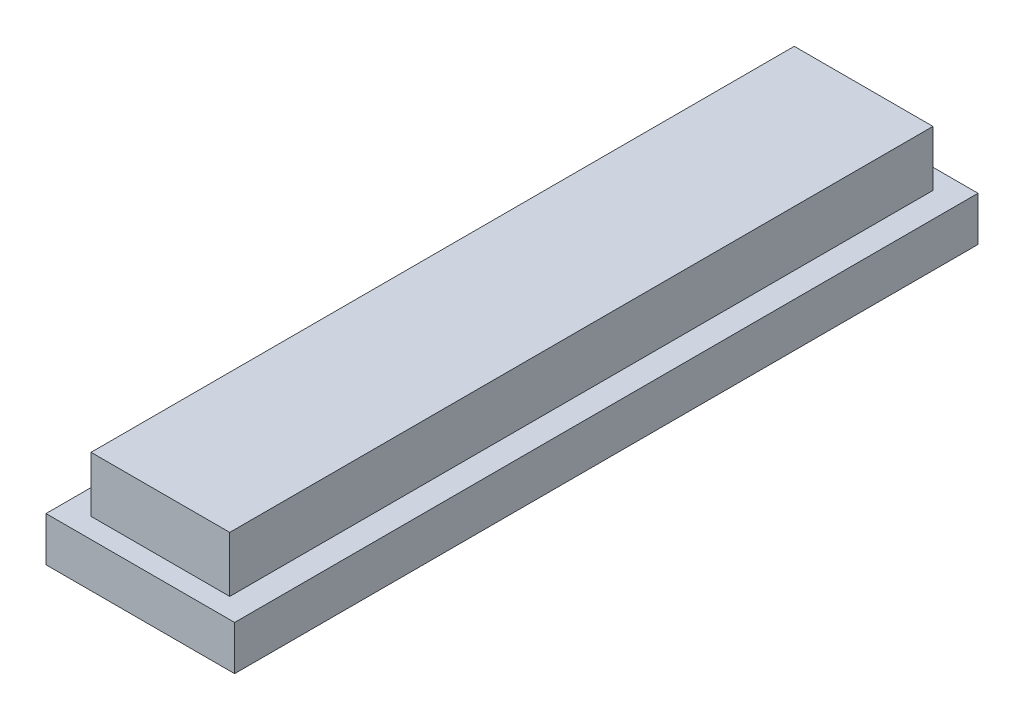
SolidWorks part; units mm, degrees
ref_plane "Front Plane" through (0, 0, 0) normal (0, 0, 1) x (1, 0, 0)
ref_plane "Top Plane" through (0, 0, 0) normal (0, 1, 0) x (1, 0, 0)
ref_plane "Right Plane" through (0, 0, 0) normal (1, 0, 0) x (0, 0, -1)
sketch "Sketch1" plane through (0, 0, 0) normal (0, 1, 0) x (1, 0, 0)
  line L1 (8.5, 33.5) -> (-8.5, 33.5)
  line L2 (8.5, 33.5) -> (8.5, -33.5)
  line L3 (8.5, -33.5) -> (-8.5, -33.5)
  line L4 (-8.5, 33.5) -> (-8.5, -33.5)
  line L5 (8.5, 33.5) -> (-8.5, -33.5) construction
  line L6 (8.5, -33.5) -> (-8.5, 33.5) construction
  point P0 (0, 0)
  dimension "D1" = 17
  dimension "D2" = 67
extrude "Boss-Extrude1" add sketch "Sketch1" along normal blind 4
sketch "Sketch2" plane through (0, 4, 0) normal (0, 1, 0) x (1, 0, 0)
  line L1 (6.25, 31.69) -> (-6.25, 31.69)
  line L2 (6.25, 31.69) -> (6.25, -31.69)
  line L3 (6.25, -31.69) -> (-6.25, -31.69)
  line L4 (-6.25, 31.69) -> (-6.25, -31.69)
  line L5 (6.25, 31.69) -> (-6.25, -31.69) construction
  line L6 (6.25, -31.69) -> (-6.25, 31.69) construction
  point P0 (0, 0)
  dimension "D1" = 12.5
  dimension "D2" = 63.38
extrude "Boss-Extrude2" add sketch "Sketch2" along normal blind 5
sketch "Sketch3" plane through (0, 0, 0) normal (0, -1, 0) x (1, 0, 0)
  circle A0 centre (0, 0) radius 3.45
  circle A1 centre (0.1368, 12.9993) radius 3.45
  circle A2 centre (0.2736, 25.9986) radius 3.45
  circle A3 centre (0.0003, -13) radius 3.45
  circle A4 centre (0.0005, -26) radius 3.45
  dimension "D1" = 6.9
  dimension "D2" = 3
  dimension "D3" = 3
extrude "Cut-Extrude1" cut sketch "Sketch3" against normal blind 1
sketch "Sketch4" plane through (0, 0, 0) normal (0, -1, 0) x (1, 0, 0)
  circle A0 centre (0, 0) radius 2.95
  circle A1 centre (0.1368, 12.9993) radius 2.95
  circle A2 centre (0.2736, 25.9986) radius 2.95
  circle A3 centre (0.0003, -13) radius 2.95
  circle A4 centre (0.0005, -26) radius 2.95
  dimension "D1" = 5.9
  dimension "D2" = 3
  dimension "D3" = 3
extrude "Cut-Extrude2" cut sketch "Sketch4" against normal blind 7.5
